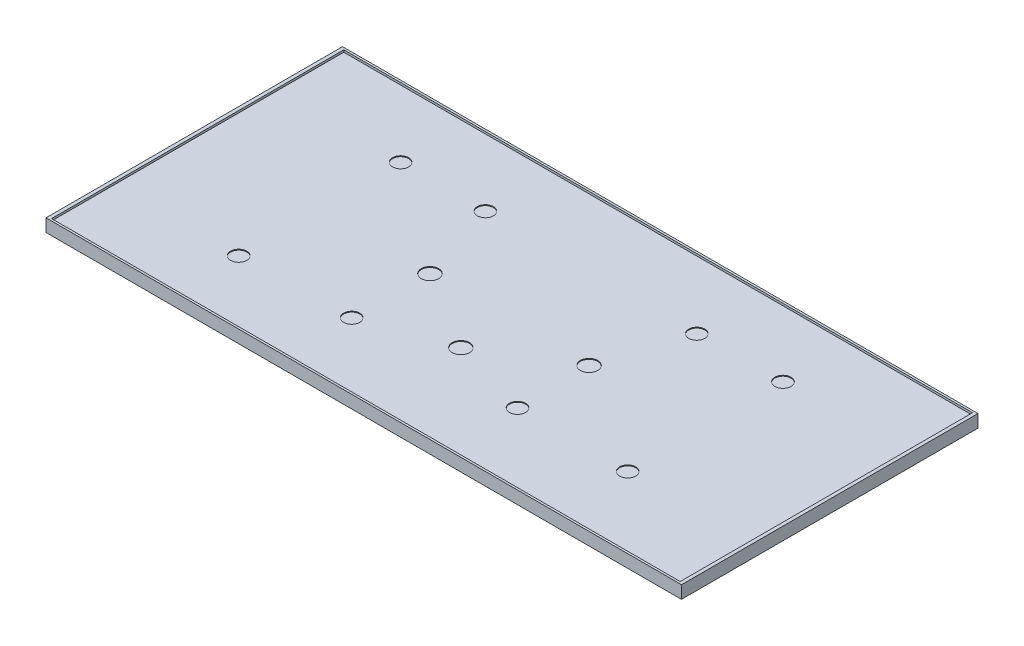
SolidWorks part; units mm, degrees
ref_plane "Front Plane" through (0, 0, 0) normal (0, 0, 1) x (1, 0, 0)
ref_plane "Top Plane" through (0, 0, 0) normal (0, 1, 0) x (1, 0, 0)
ref_plane "Right Plane" through (0, 0, 0) normal (1, 0, 0) x (0, 0, -1)
sketch "Sketch2" plane through (0, 0, 0) normal (0, 1, 0) x (1, 0, 0)
  line L1 (-302.7274, 483.0303) -> (1197.2726, 483.0303)
  line L2 (-302.7274, 483.0303) -> (-302.7274, -216.9697)
  line L3 (-302.7274, -216.9697) -> (1197.2726, -216.9697)
  line L4 (1197.2726, 483.0303) -> (1197.2726, -216.9697)
  dimension "D1" = 700
  dimension "D2" = 1500
extrude "Boss-Extrude1" add sketch "Sketch2" along normal blind 30
sketch "Sketch3" plane through (0, 30, 0) normal (0, 1, 0) x (1, 0, 0)
  line L0 (1197.2726, 483.0303) -> (-302.7274, 483.0303) construction
  line L1 (-294.7274, 478.0303) -> (1189.2726, 478.0303)
  line L2 (-294.7274, 478.0303) -> (-294.7274, -211.9697)
  line L3 (-294.7274, -211.9697) -> (1189.2726, -211.9697)
  line L4 (1189.2726, 478.0303) -> (1189.2726, -211.9697)
  line L5 (-302.7274, 483.0303) -> (-302.7274, -216.9697) construction
  line L6 (-302.7274, -216.9697) -> (1197.2726, -216.9697) construction
  line L7 (1197.2726, -216.9697) -> (1197.2726, 483.0303) construction
  dimension "D1" = 5
  dimension "D2" = 8
  dimension "D3" = 5
  dimension "D4" = 8
ref_plane "Plane1" through (-302.7274, 30, -483.0303) normal (0, 0, 1) x (1, 0, 0)
extrude "Cut-Extrude2" cut sketch "Sketch3" against normal blind 5
sketch "Sketch9" plane through (0, 25, 0) normal (0, 1, 0) x (1, 0, 0)
  circle A0 centre (197.2726, 320.1054) radius 19
  circle A1 centre (697.3005, 319.2702) radius 19
  circle A2 centre (257.2726, -55.3776) radius 19
  circle A3 centre (637.2726, -43.8826) radius 19
  circle A4 centre (259.5726, 127.1545) radius 20.5
  circle A6 centre (634.9549, 127.1545) radius 20.5
  circle A7 centre (447.2638, 12.385) radius 20.5
  circle A8 centre (-2.7274, 320.1054) radius 19
  circle A9 centre (-2.7274, -61.9697) radius 19
  circle A10 centre (897.2726, 322.6111) radius 19
  circle A11 centre (897.2726, -43.8826) radius 19
  dimension "D1" = 38
  dimension "D2" = 38
  dimension "D3" = 38
  dimension "D4" = 38
  dimension "D9" = 41
  dimension "D10" = 41
  dimension "D13" = 41
  dimension "D16" = 38
  dimension "D17" = 38
  dimension "D18" = 38
  dimension "D19" = 38
  dimension "D14" = 220
  dimension "D15" = 220
  dimension "D20" = 200
  dimension "D21" = 200
  dimension "D22" = 260
  dimension "D23" = 260
extrude "Cut-Extrude3" cut sketch "Sketch9" against normal blind 2
